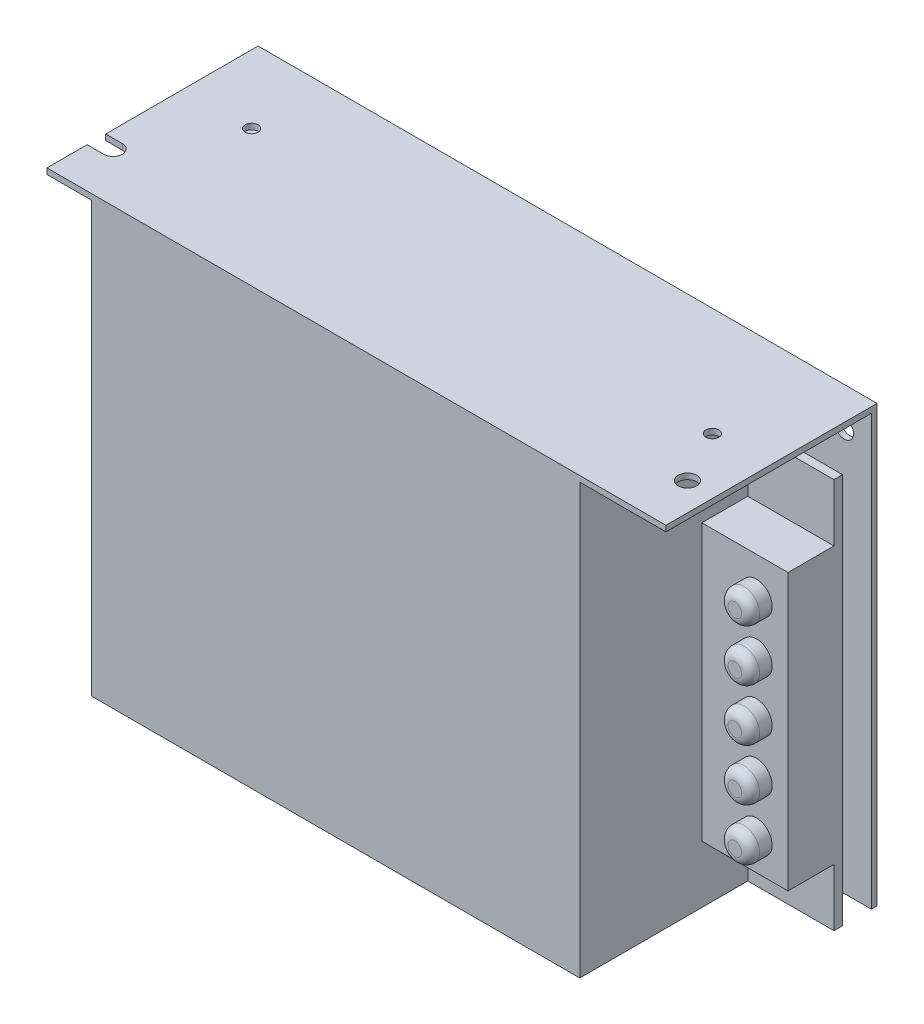
SolidWorks part; units mm, degrees
ref_plane "Front Plane" through (0, 0, 0) normal (0, 0, 1) x (1, 0, 0)
ref_plane "Top Plane" through (0, 0, 0) normal (0, 1, 0) x (1, 0, 0)
ref_plane "Right Plane" through (0, 0, 0) normal (1, 0, 0) x (0, 0, -1)
sketch "Sketch1" plane through (0, 0, 0) normal (0, 0, 1) x (1, 0, 0)
  line L1 (0, 0) -> (109.474, 0)
  line L2 (0, 0) -> (0, 76.962)
  line L3 (0, 76.962) -> (109.474, 76.962)
  line L4 (109.474, 0) -> (109.474, 76.962)
  dimension "D1" = 109.474
  dimension "D2" = 76.962
extrude "Boss-Extrude1" add sketch "Sketch1" along normal blind 1.016
sketch "Sketch2" plane through (0, 0, 1.016) normal (0, 0, 1) x (1, 0, 0)
  line L0 (109.474, 0) -> (109.474, 76.962) construction
  line L1 (0, 76.962) -> (109.474, 76.962)
  line L2 (0, 76.962) -> (0, 75.946)
  line L3 (0, 75.946) -> (109.474, 75.946)
  line L4 (109.474, 76.962) -> (109.474, 75.946)
  dimension "D1" = 1.016
extrude "Boss-Extrude2" add sketch "Sketch2" along normal blind 36.322
sketch "Sketch3" plane through (0, 0, 1.016) normal (0, 0, 1) x (1, 0, 0)
  line L0 (103.0478, 71.2343) -> (109.474, 71.2343) construction
  line L1 (109.474, 0) -> (109.474, 75.946) construction
  line L2 (104.6861, 69.596) -> (104.6861, 75.946) construction
  line L3 (0, 75.946) -> (109.474, 75.946) construction
  line L6 (4.064, 4.1275) -> (0, 4.1275) construction
  line L7 (0, 75.946) -> (0, 0) construction
  line L8 (2.2225, 2.286) -> (0, 2.286)
  line L9 (0, 2.286) -> (0, 5.969)
  line L10 (0, 5.969) -> (2.2225, 5.969)
  line L11 (0, 0) -> (109.474, 0) construction
  line L12 (4.064, 4.1275) -> (103.0478, 71.2343) construction
  circle A0 centre (104.6861, 71.2343) radius 1.6383
  arc A1 (2.2225, 2.286) -> (2.2225, 5.969) centre (2.2225, 4.1275) ccw
  dimension "D1" = 3.2766
  dimension "D4" = 3.683
  dimension "D2" = 6.4262
  dimension "D3" = 6.35
  dimension "D5" = 4.064
  dimension "D6" = 2.286
  dimension "D7" = 119.5873
extrude "Cut-Extrude1" cut sketch "Sketch3" against normal through all
sketch "Sketch4" plane through (0, 0, 1.016) normal (0, 0, 1) x (1, 0, 0)
  line L0 (0, 75.946) -> (109.474, 75.946) construction
  line L1 (7.874, 75.946) -> (94.234, 75.946)
  line L2 (7.874, 75.946) -> (7.874, 0)
  line L3 (7.874, 0) -> (94.234, 0)
  line L4 (94.234, 75.946) -> (94.234, 0)
  line L5 (0, 0) -> (109.474, 0) construction
  line L6 (109.474, 0) -> (109.474, 75.946) construction
  dimension "D1" = 86.36
  dimension "D2" = 15.24
extrude "Boss-Extrude3" add sketch "Sketch4" along normal up to surface (36.322 mm away) up to face at (54.737, 76.454, 37.338)
sketch "Sketch5" plane through (0, 76.962, 0) normal (0, 1, 0) x (1, 0, 0)
  line L0 (106.172, -28.5877) -> (109.474, -28.5877) construction
  line L1 (109.474, -37.338) -> (109.474, 0) construction
  line L2 (104.5337, -30.226) -> (104.5337, -37.338) construction
  line L3 (109.474, -37.338) -> (0, -37.338) construction
  line L4 (2.9337, -28.5877) -> (104.5337, -28.5877) construction
  line L5 (4.572, -28.5877) -> (0, -28.5877) construction
  line L6 (0, -37.338) -> (0, 0) construction
  line L7 (2.9337, -26.9494) -> (0, -26.9494)
  line L8 (0, -26.9494) -> (0, -30.226)
  line L9 (0, -30.226) -> (2.9337, -30.226)
  line L10 (100.6856, -19.177) -> (109.474, -19.177) construction
  line L11 (99.5426, -20.32) -> (99.5426, -37.338) construction
  line L12 (10.922, -13.208) -> (0, -13.208) construction
  line L13 (12.065, -12.065) -> (12.065, 0) construction
  line L14 (109.474, 0) -> (0, 0) construction
  line L15 (13.208, -13.208) -> (98.3996, -19.177) construction
  circle A0 centre (104.5337, -28.5877) radius 1.6383
  arc A1 (2.9337, -30.226) -> (2.9337, -26.9494) centre (2.9337, -28.5877) ccw
  circle A2 centre (99.5426, -19.177) radius 1.143
  circle A3 centre (12.065, -13.208) radius 1.143
  dimension "D1" = 3.2766
  dimension "D4" = 3.2766
  dimension "D6" = 2.286
  dimension "D7" = 2.286
  dimension "D2" = 3.302
  dimension "D3" = 7.112
  dimension "D5" = 4.572
  dimension "D8" = 8.7884
  dimension "D9" = 17.018
  dimension "D10" = 10.922
  dimension "D11" = 12.065
  dimension "D12" = 85.4005
extrude "Cut-Extrude2" cut sketch "Sketch5" against normal up to surface (1.016 mm away) up to face at (3.937, 75.946, 19.177)
sketch "Sketch6" plane through (0, 0, 0) normal (0, 0, -1) x (-1, 0, 0)
  line L0 (-76.9874, 24.8412) -> (-43.4594, 24.8412) construction
  line L1 (-42.3164, 51.3842) -> (-42.3164, 25.9842) construction
  line L2 (-42.3164, 53.6702) -> (-42.3164, 76.962) construction
  line L3 (-109.474, 76.962) -> (0, 76.962) construction
  line L4 (-42.3164, 23.6982) -> (-42.3164, 0) construction
  line L5 (-79.2734, 24.8412) -> (-109.474, 24.8412) construction
  line L6 (-109.474, 0) -> (-109.474, 76.962) construction
  line L7 (0, 0) -> (-109.474, 0) construction
  circle A0 centre (-78.1304, 24.8412) radius 1.143
  circle A1 centre (-42.3164, 24.8412) radius 1.143
  circle A2 centre (-42.3164, 52.5272) radius 1.143
  point P18 (-109.474, 32.0493)
  point P21 (-42.545, 0)
  dimension "D1" = 2.286
  dimension "D2" = 25.4
  dimension "D3" = 33.528
  dimension "D4" = 23.6982
  dimension "D5" = 30.2006
  dimension "D6" = 66.0146
  dimension "D7" = 51.3842
extrude "Cut-Extrude3" cut sketch "Sketch6" against normal blind 6.35
sketch "Sketch7" plane through (94.234, 0, 0) normal (1, 0, 0) x (0, 0, -1)
  line L0 (-37.338, 75.946) -> (-1.016, 75.946) construction
  line L1 (-7.62, 75.946) -> (-6.096, 75.946)
  line L2 (-7.62, 75.946) -> (-7.62, 0)
  line L3 (-7.62, 0) -> (-6.096, 0)
  line L4 (-6.096, 75.946) -> (-6.096, 0)
  line L5 (-37.338, 0) -> (-1.016, 0) construction
  line L6 (0, 0) -> (0, 76.962) construction
  dimension "D1" = 1.524
  dimension "D2" = 7.62
extrude "Boss-Extrude4" add sketch "Sketch7" along normal up to surface (15.24 mm away) up to face at (109.474, 50.9693, 12.7847)
sketch "Sketch8" plane through (0, 0, 7.62) normal (0, 0, 1) x (1, 0, 0)
  line L0 (94.234, 75.946) -> (109.474, 75.946) construction
  line L1 (101.854, 75.946) -> (109.474, 75.946)
  line L2 (101.854, 75.946) -> (101.854, 69.088)
  line L3 (101.854, 69.088) -> (109.474, 69.088)
  line L4 (109.474, 75.946) -> (109.474, 69.088)
  line L5 (109.474, 0) -> (109.474, 75.946) construction
  dimension "D1" = 6.858
extrude "Cut-Extrude4" cut sketch "Sketch8" against normal up to next
sketch "Sketch9" plane through (0, 0, 7.62) normal (0, 0, 1) x (1, 0, 0)
  line L0 (94.234, 0) -> (94.234, 75.946) construction
  line L1 (94.234, 58.928) -> (109.474, 58.928)
  line L2 (94.234, 58.928) -> (94.234, 10.16)
  line L3 (94.234, 10.16) -> (109.474, 10.16)
  line L4 (109.474, 58.928) -> (109.474, 10.16)
  line L5 (109.474, 0) -> (109.474, 69.088) construction
  line L6 (109.474, 0) -> (94.234, 0) construction
  dimension "D1" = 48.768
  dimension "D2" = 10.16
extrude "Boss-Extrude5" add sketch "Sketch9" along normal blind 8.128
sketch "Sketch10" plane through (0, 0, 15.748) normal (0, 0, 1) x (1, 0, 0)
  line L0 (94.234, 10.16) -> (109.474, 10.16) construction
  line L2 (109.474, 10.16) -> (109.474, 58.928) construction
  circle A0 centre (103.886, 15.748) radius 2.794
  point P6 (109.474, 15.2779)
  dimension "D1" = 5.588
  dimension "D2" = 5.588
  dimension "D3" = 5.588
extrude "Boss-Extrude6" add sketch "Sketch10" along normal blind 3.81
fillet "Fillet1" radius 1.5875 1 edges at (106.68, 15.748, 19.558)
pattern_linear "LPattern2" count 5 spacing 9.144 along (0, 1, 0) of "Fillet1", "Boss-Extrude6"
sketch "Sketch11" plane through (0, 75.946, 0) normal (0, -1, 0) x (1, 0, 0)
  line L0 (7.874, 1.016) -> (0, 1.016)
  line L1 (0, 1.016) -> (0, 6.096)
  line L2 (0, 26.9494) -> (0, 1.016) construction
  line L4 (7.874, 37.338) -> (7.874, 1.016) construction
  line L5 (7.874, 11.176) -> (7.874, 1.016)
  line L6 (7.874, 11.176) -> (0, 6.096)
  dimension "D1" = 10.16
  dimension "D2" = 5.08
extrude "Boss-Extrude7" add sketch "Sketch11" along normal offset from surface (65.786 mm away) 10.16 up to face at (69.215, 0, 8.8477)
